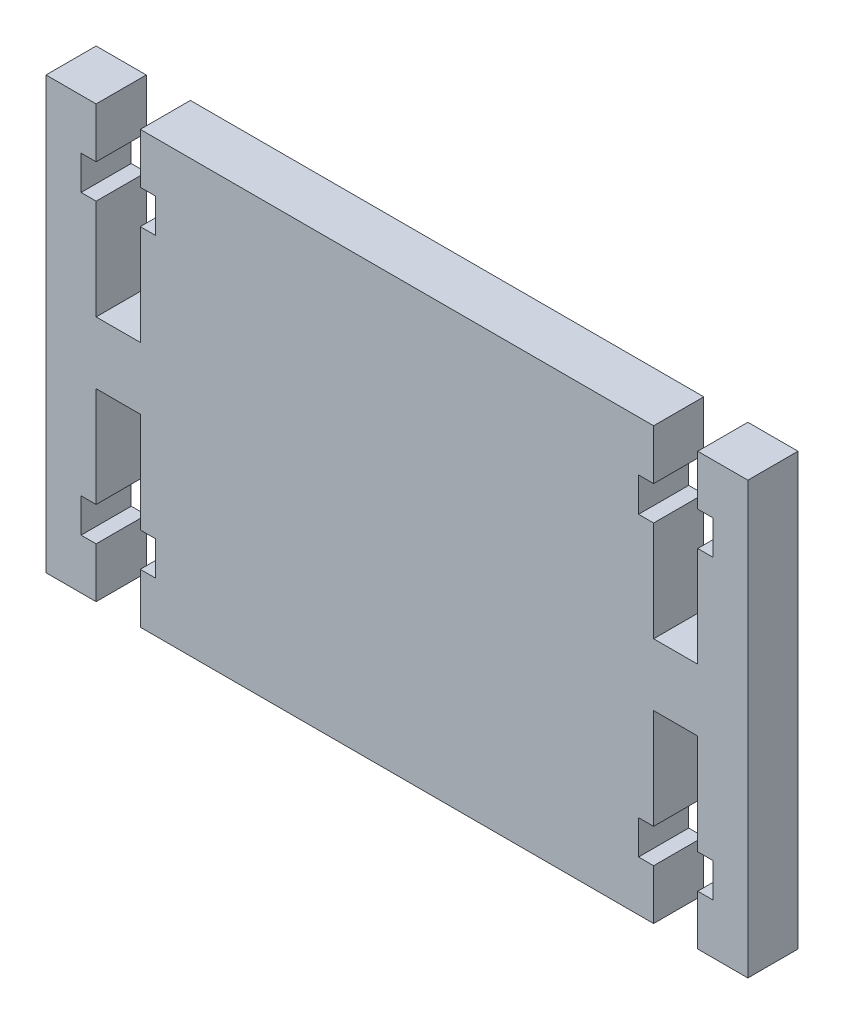
SolidWorks part; units mm, degrees
ref_plane "Front Plane" through (0, 0, 0) normal (0, 0, 1) x (1, 0, 0)
ref_plane "Top Plane" through (0, 0, 0) normal (0, 1, 0) x (1, 0, 0)
ref_plane "Right Plane" through (0, 0, 0) normal (1, 0, 0) x (0, 0, -1)
sketch "Sketch1" plane through (0, 0, 0) normal (0, 0, 1) x (1, 0, 0)
  line L1 (-35, 21.5) -> (35, 21.5)
  line L2 (-35, 21.5) -> (-35, -21.5)
  line L3 (-35, -21.5) -> (35, -21.5)
  line L4 (35, 21.5) -> (35, -21.5)
  dimension "D1" = 43
  dimension "D2" = 70
  dimension "D3" = 35
  dimension "D4" = 21.5
extrude "Boss-Extrude1" add sketch "Sketch1" along normal blind 5
sketch "Sketch3" plane through (0, 0, 5) normal (0, 0, 1) x (1, 0, 0)
  line L0 (-27.8, 1.3) -> (-27.8, 16.1452) construction
  line L1 (-25.6, 13.1) -> (-25.6, 3.1)
  line L2 (-30, 16.5) -> (-30, 21.5)
  line L3 (-24.1, 16.5) -> (-25.6, 16.5)
  line L4 (-24.1, 13.1) -> (-24.1, 16.5)
  line L5 (-25.6, 13.1) -> (-24.1, 13.1)
  line L6 (-31.5, 16.5) -> (-30, 16.5)
  line L7 (-31.5, 13.1) -> (-31.5, 16.5)
  line L8 (-30, 13.1) -> (-31.5, 13.1)
  line L9 (-30, 3.1) -> (-25.6, 3.1)
  line L10 (-25.6, 21.5) -> (-25.6, 16.5)
  line L11 (-30, 21.5) -> (-25.6, 21.5)
  line L12 (-30, 3.1) -> (-30, 13.1)
  line L13 (35, 21.5) -> (-35, 21.5) construction
  line L14 (-35, 21.5) -> (-35, -21.5) construction
  line L15 (0, 21.5) -> (0, -21.5) construction
  line L16 (-35, -21.5) -> (35, -21.5) construction
  line L17 (0, 0) -> (27.1593, 0) construction
  line L18 (27.8, 1.3) -> (27.8, 16.1452) construction
  line L19 (30, 3.1) -> (30, 13.1)
  line L20 (30, 21.5) -> (25.6, 21.5)
  line L21 (25.6, 21.5) -> (25.6, 16.5)
  line L22 (30, 3.1) -> (25.6, 3.1)
  line L23 (30, 13.1) -> (31.5, 13.1)
  line L24 (31.5, 13.1) -> (31.5, 16.5)
  line L25 (31.5, 16.5) -> (30, 16.5)
  line L26 (25.6, 13.1) -> (24.1, 13.1)
  line L27 (24.1, 13.1) -> (24.1, 16.5)
  line L28 (24.1, 16.5) -> (25.6, 16.5)
  line L29 (30, 16.5) -> (30, 21.5)
  line L30 (25.6, 13.1) -> (25.6, 3.1)
  line L31 (27.8, -1.3) -> (27.8, -16.1452) construction
  line L32 (25.6, -13.1) -> (25.6, -3.1)
  line L33 (30, -16.5) -> (30, -21.5)
  line L34 (24.1, -16.5) -> (25.6, -16.5)
  line L35 (24.1, -13.1) -> (24.1, -16.5)
  line L36 (25.6, -13.1) -> (24.1, -13.1)
  line L37 (31.5, -16.5) -> (30, -16.5)
  line L38 (31.5, -13.1) -> (31.5, -16.5)
  line L39 (30, -13.1) -> (31.5, -13.1)
  line L40 (30, -3.1) -> (25.6, -3.1)
  line L41 (25.6, -21.5) -> (25.6, -16.5)
  line L42 (30, -21.5) -> (25.6, -21.5)
  line L43 (30, -3.1) -> (30, -13.1)
  line L44 (-27.8, -1.3) -> (-27.8, -16.1452) construction
  line L45 (-30, -3.1) -> (-30, -13.1)
  line L46 (-30, -21.5) -> (-25.6, -21.5)
  line L47 (-25.6, -21.5) -> (-25.6, -16.5)
  line L48 (-30, -3.1) -> (-25.6, -3.1)
  line L49 (-30, -13.1) -> (-31.5, -13.1)
  line L50 (-31.5, -13.1) -> (-31.5, -16.5)
  line L51 (-31.5, -16.5) -> (-30, -16.5)
  line L52 (-25.6, -13.1) -> (-24.1, -13.1)
  line L53 (-24.1, -13.1) -> (-24.1, -16.5)
  line L54 (-24.1, -16.5) -> (-25.6, -16.5)
  line L55 (-30, -16.5) -> (-30, -21.5)
  line L56 (-25.6, -13.1) -> (-25.6, -3.1)
  dimension "D1" = 5
  dimension "D2" = 3.4
  dimension "D3" = 10
  dimension "D4" = 2.2
  dimension "D5" = 4.4
  dimension "D6" = 1.5
  dimension "D7" = 1.5
  dimension "D8" = 5
extrude "Cut-Extrude1" cut sketch "Sketch3" against normal blind 5
